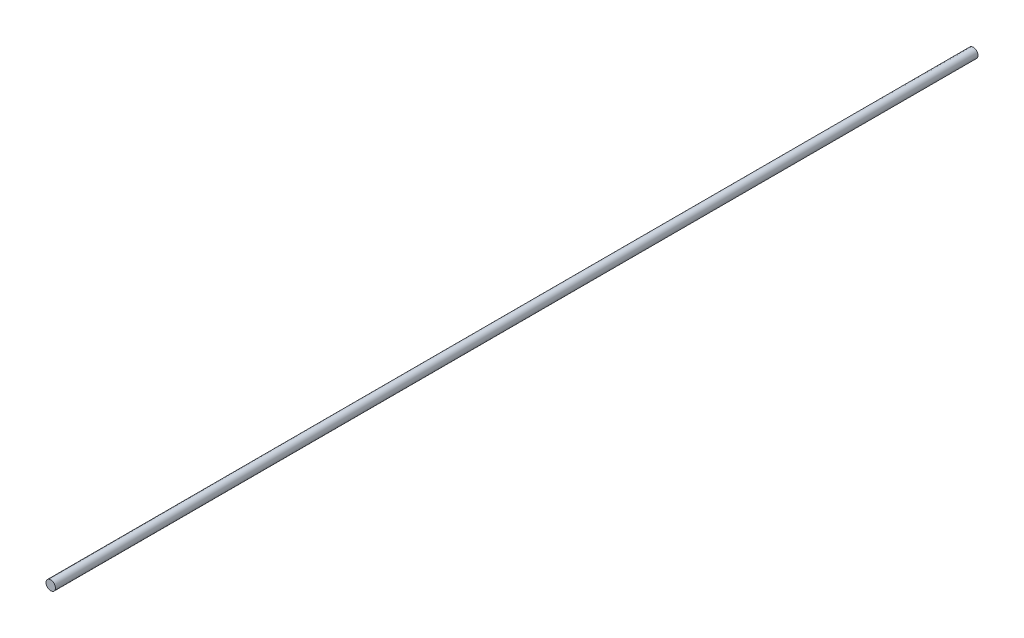
SolidWorks part; units mm, degrees
ref_plane "Piano frontale" through (0, 0, 0) normal (0, 0, 1) x (1, 0, 0)
ref_plane "Piano superiore" through (0, 0, 0) normal (0, 1, 0) x (1, 0, 0)
ref_plane "Piano destro" through (0, 0, 0) normal (1, 0, 0) x (0, 0, -1)
sketch "Schizzo1" plane through (0, 0, 0) normal (0, 0, 1) x (1, 0, 0)
  circle A0 centre (0, 0) radius 1
  dimension "D1" = 2
extrude "Estrusione-Estrusione1" add sketch "Schizzo1" along normal blind 195
